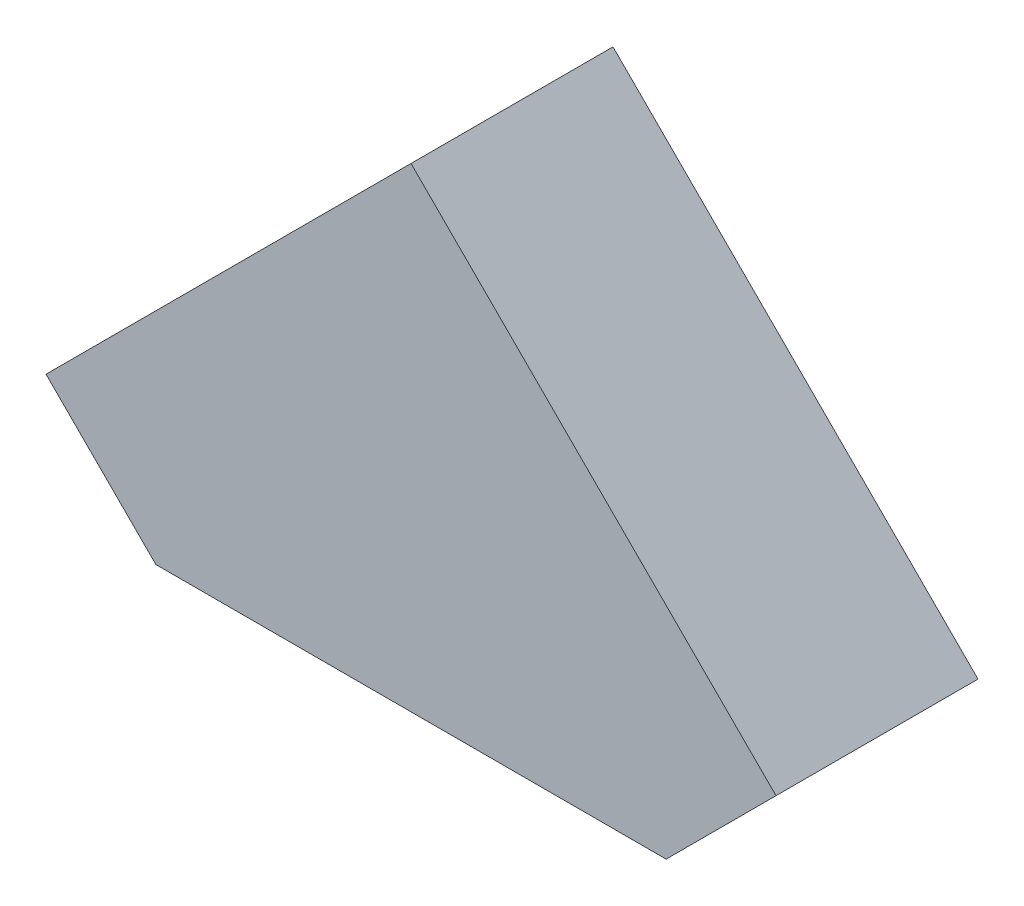
SolidWorks part; units mm, degrees
ref_plane "Спереди" through (0, 0, 0) normal (0, 0, 1) x (1, 0, 0)
ref_plane "Сверху" through (0, 0, 0) normal (0, 1, 0) x (1, 0, 0)
ref_plane "Справа" through (0, 0, 0) normal (1, 0, 0) x (0, 0, -1)
sketch "Эскиз1" plane through (0, 0, 0) normal (0, 0, 1) x (1, 0, 0)
  line L0 (-17, -12) -> (17, -12)
  line L1 (17, -12) -> (23.0901, -5.9099)
  line L2 (23.0901, -5.9099) -> (0, 17.1802)
  line L3 (0, 17.1802) -> (-23.0901, -5.9099)
  line L4 (-23.0901, -5.9099) -> (-17, -12)
  line L5 (16.5, -10.5) -> (-16.5, -10.5) construction
  dimension "D1" = 90
  dimension "D2" = 90
  dimension "D3" = 90
  dimension "D4" = 1.5
  dimension "D5" = 0.5
  dimension "D6" = 0.5
extrude "Вытянуть-Тонкостенный1" add sketch "Эскиз1" along normal blind 12.75 and the other way blind 12.75 thin
sketch "Эскиз2" plane through (0, 0, 12.75) normal (0, 0, 1) x (1, 0, 0)
  line L0 (25.2114, -5.9099) -> (0, 19.3015) construction
  line L1 (17.6213, -13.5) -> (25.2114, -5.9099) construction
  line L2 (-17.6213, -13.5) -> (17.6213, -13.5) construction
  line L3 (-25.2114, -5.9099) -> (-17.6213, -13.5) construction
  line L4 (0, 19.3015) -> (-25.2114, -5.9099) construction
  line L5 (25.2114, -5.9099) -> (0, 19.3015)
  line L6 (17.6213, -13.5) -> (25.2114, -5.9099)
  line L7 (-17.6213, -13.5) -> (17.6213, -13.5)
  line L8 (-25.2114, -5.9099) -> (-17.6213, -13.5)
  line L9 (0, 19.3015) -> (-25.2114, -5.9099)
extrude "Бобышка-Вытянуть1" add sketch "Эскиз2" along normal blind 1.2
sketch "Эскиз3" plane through (0, 0, -12.75) normal (0, 0, -1) x (-1, 0, 0)
  line L0 (0, 19.3015) -> (25.2114, -5.9099) construction
  line L1 (25.2114, -5.9099) -> (17.6213, -13.5) construction
  line L2 (17.6213, -13.5) -> (-17.6213, -13.5) construction
  line L3 (-17.6213, -13.5) -> (-25.2114, -5.9099) construction
  line L4 (-25.2114, -5.9099) -> (0, 19.3015) construction
  line L5 (0, 19.3015) -> (25.2114, -5.9099)
  line L6 (25.2114, -5.9099) -> (17.6213, -13.5)
  line L7 (17.6213, -13.5) -> (-17.6213, -13.5)
  line L8 (-17.6213, -13.5) -> (-25.2114, -5.9099)
  line L9 (-25.2114, -5.9099) -> (0, 19.3015)
extrude "Бобышка-Вытянуть2" add sketch "Эскиз3" along normal blind 1.2
sketch "Эскиз4" plane through (0, -13.5, 0) normal (0, -1, 0) x (1, 0, 0)
  line L0 (11.5, 11.5) -> (-11.5, 11.5) construction
  line L1 (-11.8, 11.8) -> (11.8, 11.8)
  line L2 (-11.8, 11.8) -> (-11.8, -11.8)
  line L3 (-11.8, -11.8) -> (11.8, -11.8)
  line L4 (11.8, 11.8) -> (11.8, -11.8)
  line L5 (-11.8, 11.8) -> (11.8, -11.8) construction
  line L6 (-11.8, -11.8) -> (11.8, 11.8) construction
  line L7 (11.5, -11.5) -> (11.5, 11.5) construction
  point P0 (0, 0)
  dimension "D1" = 0.3
  dimension "D2" = 0.3
extrude "Вырез-Вытянуть1" cut sketch "Эскиз4" against normal up to surface (1.5 mm away) up to face at (0, -12, 0)
sketch "Эскиз5" plane through (0, 0, 0) normal (1, 0, 0) x (0, 0, -1)
  line L0 (13.95, 19.3015) -> (-13.95, 19.3015) construction
  line L1 (0, 19.3015) -> (13.95, 19.3015)
  line L2 (0, 19.3015) -> (0, -13.5)
  line L3 (0, -13.5) -> (13.95, -13.5)
  line L4 (13.95, 19.3015) -> (13.95, -13.5)
extrude "Вырез-Вытянуть2" cut sketch "Эскиз5" against normal through all and the other way through all
